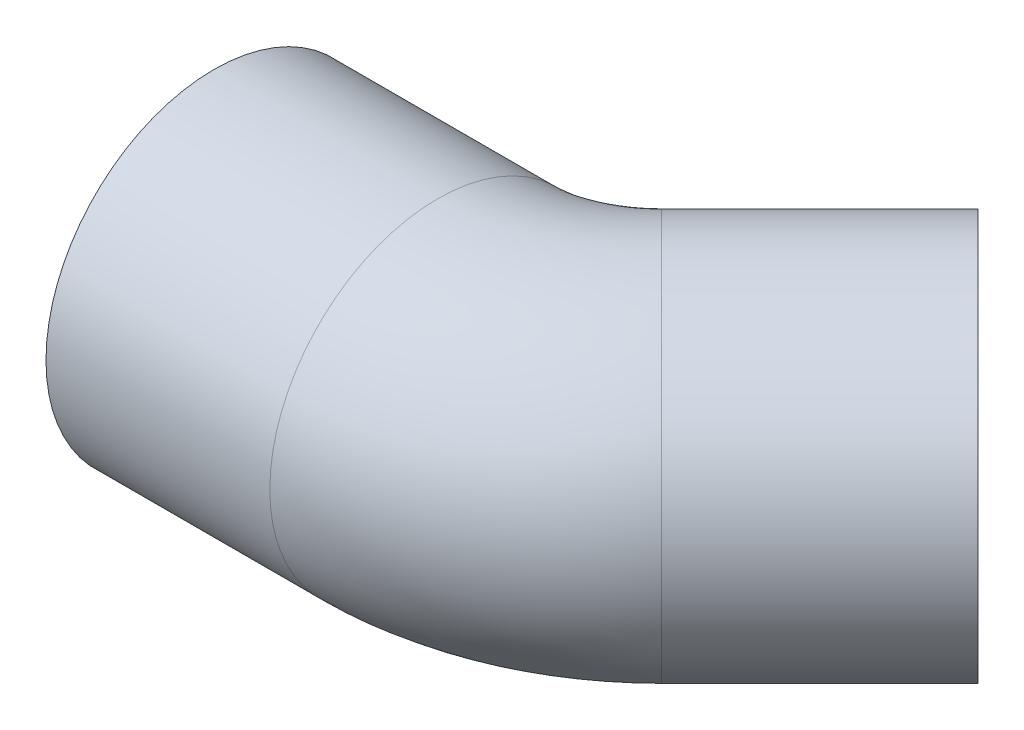
SolidWorks part; units mm, degrees
ref_plane "Front Plane" through (0, 0, 0) normal (0, 0, 1) x (1, 0, 0)
ref_plane "Top Plane" through (0, 0, 0) normal (0, 1, 0) x (1, 0, 0)
ref_plane "Right Plane" through (0, 0, 0) normal (1, 0, 0) x (0, 0, -1)
sketch "Sketch1" plane through (0, 0, 0) normal (0, 1, 0) x (1, 0, 0)
  line L0 (0, 0) -> (12.7, 0)
  line L1 (21.6803, 3.7197) -> (30.6605, 12.7)
  arc A0 (12.7, 0) -> (21.6803, 3.7197) centre (12.7, 12.7) ccw
  point P6 (0, 0)
  point P7 (0, 0)
  dimension "D1" = 135
  dimension "D4" = 12.7
  dimension "D2" = 12.7
  dimension "D3" = 12.7
sketch "Sketch2" plane through (0, 0, 0) normal (1, 0, 0) x (0, 0, -1)
  circle A0 centre (0, 0) radius 9.525
  dimension "D1" = 19.05
sweep "Sweep1" add profiles "Sketch2" path "Sketch1"
